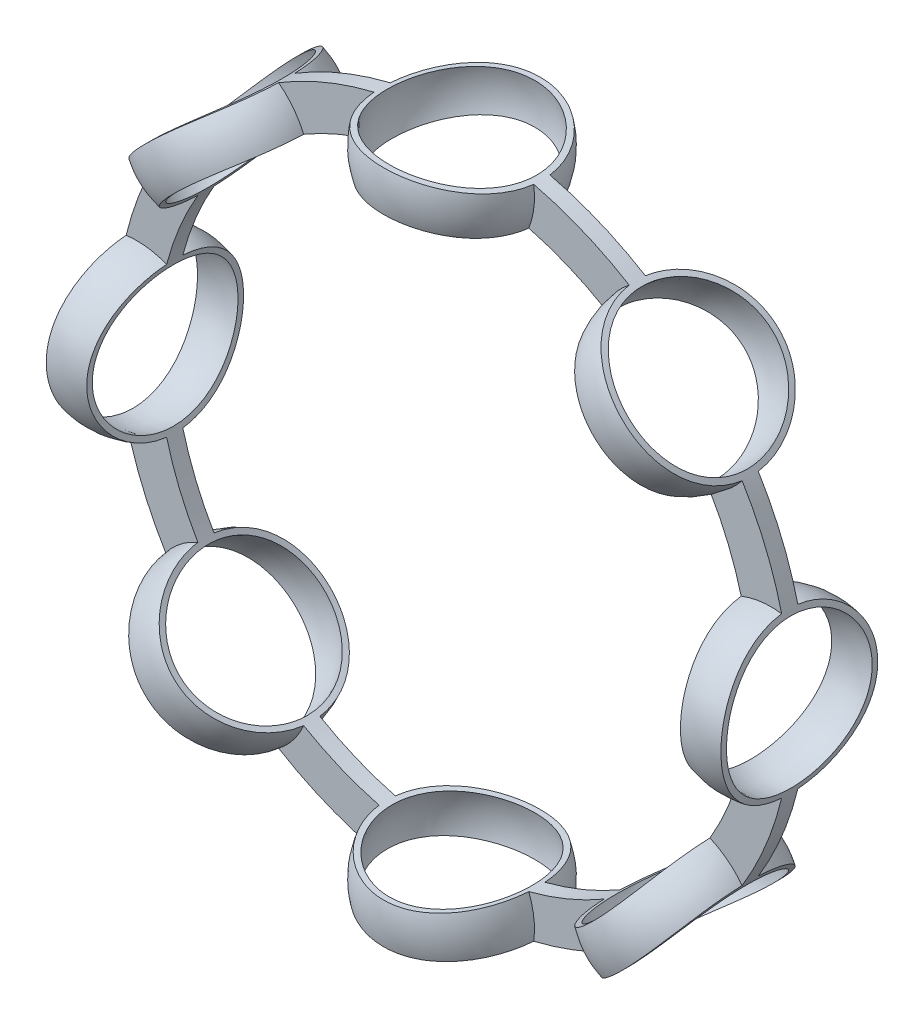
SolidWorks part; units mm, degrees
other "阵列(圆周)2"
material "锻制不锈钢"
ref_plane "前视基准面" through (0, 0, 0) normal (0, 0, 1) x (1, 0, 0)
ref_plane "上视基准面" through (0, 0, 0) normal (0, 1, 0) x (1, 0, 0)
ref_plane "右视基准面" through (0, 0, 0) normal (1, 0, 0) x (0, 0, -1)
sketch "草图1" plane through (0, 0, 0) normal (0, 0, 1) x (1, 0, 0)
  circle A0 centre (0, 0) radius 80
  dimension "D1" = 160
extrude "拉伸1" add sketch "草图1" along normal mid plane 3
sketch "草图4" plane through (0, 0, 0) normal (0, 1, 0) x (1, 0, 0)
  line L0 (58.75, 39.6642) -> (58.75, -39.6642) construction
  line L1 (58.75, 15) -> (58.75, -15)
  arc A0 (58.75, -15) -> (58.75, 15) centre (58.75, 0) ccw
  dimension "D1" = 30
  dimension "D2" = 58.75
revolve "旋转1" add sketch "草图4" angle 360 about L0
pattern_circular "阵列(圆周)1" count 8 over 360 about axis through (0, 0, 0) along (0, 0, 1) of "旋转1"
sketch "草图5" plane through (0, 0, 0) normal (0, 0, 1) x (1, 0, 0)
  circle A0 centre (0, 0) radius 62.5
  circle A1 centre (0, 0) radius 55
  dimension "D1" = 125
  dimension "D2" = 110
extrude "切除-拉伸1" cut sketch "草图5" against normal mid plane 70 flip side to cut
sketch "草图7" plane through (0, 0, 0) normal (0, 1, 0) x (1, 0, 0)
  line L0 (58.75, 25.5802) -> (58.75, -26.3487) construction
  line L1 (58.75, 14) -> (58.75, -14)
  arc A0 (58.75, -14) -> (58.75, 14) centre (58.75, 0) ccw
  dimension "D1" = 28
  dimension "D2" = 58.75
revolve "切除-旋转1" cut sketch "草图7" angle 360 about L0
pattern_circular "阵列(圆周)2" count 8 over 360 about axis through (0, 0, 0) along (0, 0, 1) of "切除-旋转1"
